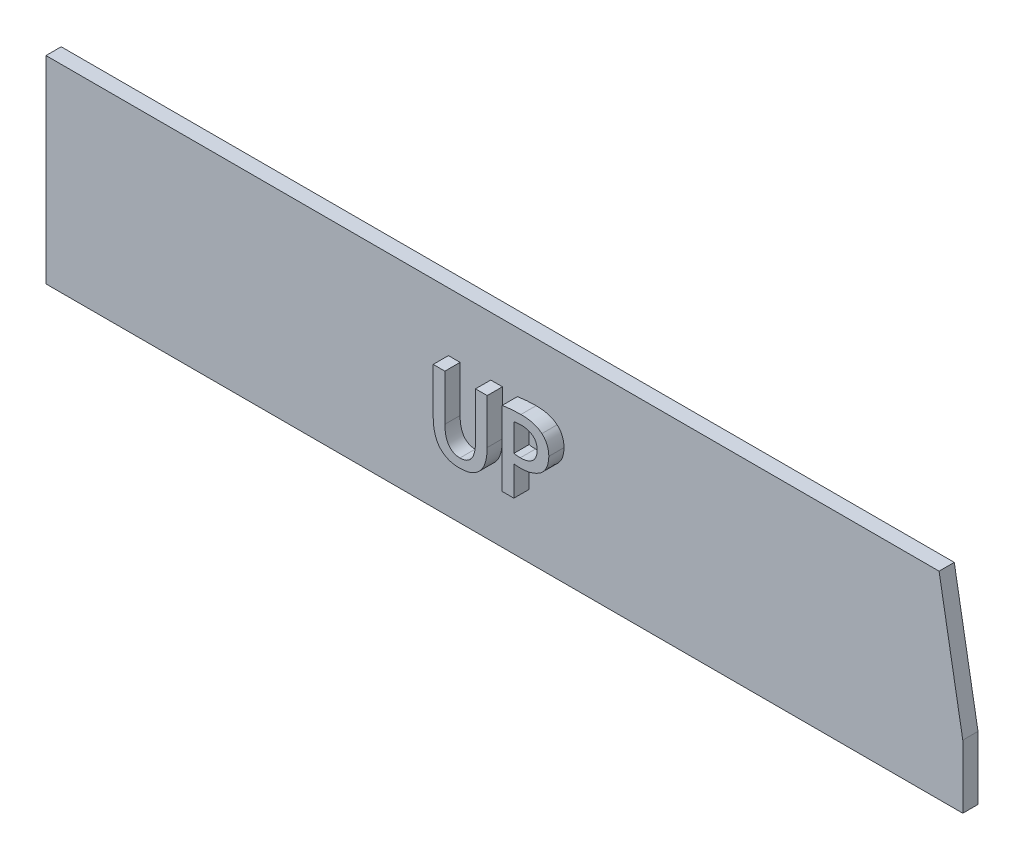
SolidWorks part; units mm, degrees
ref_plane "前视基准面" through (0, 0, 0) normal (0, 0, 1) x (1, 0, 0)
ref_plane "上视基准面" through (0, 0, 0) normal (0, 1, 0) x (1, 0, 0)
ref_plane "右视基准面" through (0, 0, 0) normal (1, 0, 0) x (0, 0, -1)
other "Configuration Table"
sketch "草图1" plane through (0, 0, 0) normal (0, 0, 1) x (1, 0, 0)
  line L0 (-21.5, 15) -> (-21.5, 0)
  line L1 (39.0308, 15) -> (-21.5, 15)
  line L2 (40.75, 5.25) -> (39.0308, 15)
  line L3 (40.75, 0) -> (40.75, 5.25)
  line L4 (-21.5, 0) -> (40.75, 0)
  circle A0 centre (19, 10) radius 2.15
  circle A1 centre (-19, 10) radius 2.15
sketch "草图2" plane through (0, 0, 0) normal (0, 0, 1) x (1, 0, 0)
  line L20 (-20.5, 1) -> (39.75, 1)
  line L21 (39.75, 1) -> (39.75, 5.1625)
  line L22 (39.75, 5.1625) -> (38.1917, 14)
  line L23 (38.1917, 14) -> (-20.5, 14)
  line L24 (-20.5, 14) -> (-20.5, 1)
  line L25 (-20.5, 1) -> (39.75, 1)
  line L26 (39.75, 1) -> (39.75, 5.1625)
  line L27 (39.75, 5.1625) -> (38.1917, 14)
  line L28 (38.1917, 14) -> (-20.5, 14)
  line L29 (-20.5, 14) -> (-20.5, 1)
  dimension "D1" = 1
extrude "凸台-拉伸1" add sketch "草图2" along normal blind 1
sketch "草图3" plane through (0, 0, 1) normal (0, 0, 1) x (1, 0, 0)
  line L0 (39.75, 5.1625) -> (-20.5, 5.1625) construction
  line L1 (-20.5, 14) -> (-20.5, 1) construction
  text T0 "UP" font "@Adobe 繁黑體 Std B" height 5
extrude "凸台-拉伸2" add sketch "草图3" along normal blind 1
